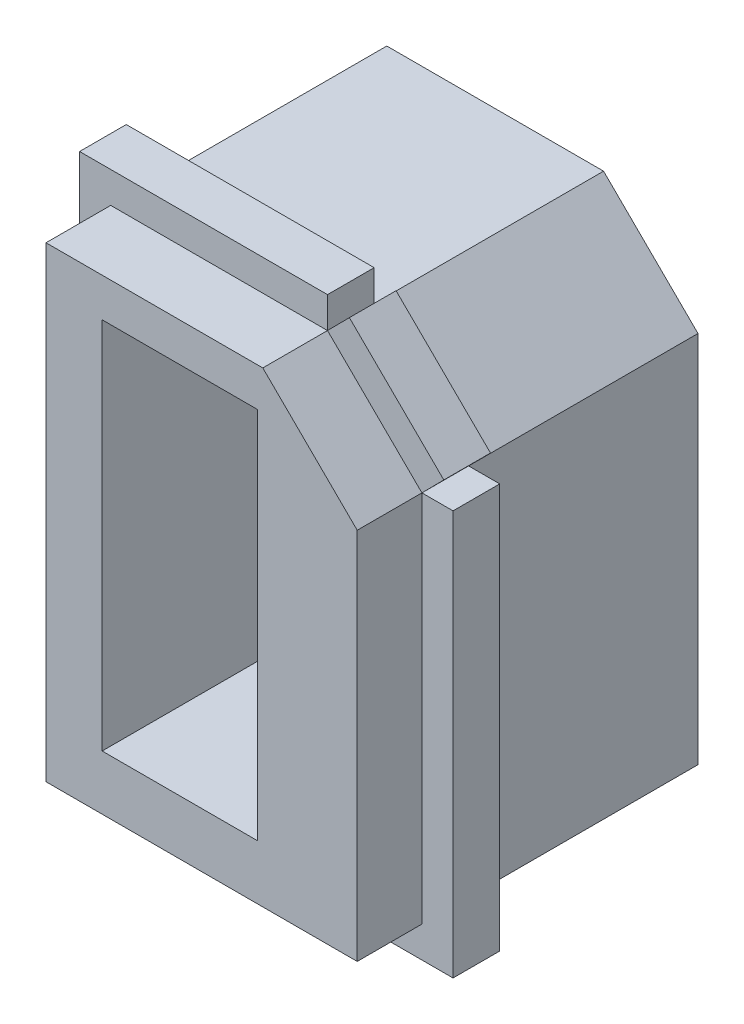
SolidWorks part; units mm, degrees
ref_plane "Front Plane" through (0, 0, 0) normal (0, 0, 1) x (1, 0, 0)
ref_plane "Top Plane" through (0, 0, 0) normal (0, 1, 0) x (1, 0, 0)
ref_plane "Right Plane" through (0, 0, 0) normal (1, 0, 0) x (0, 0, -1)
sketch "Sketch1" plane through (0, 0, 0) normal (0, 0, 1) x (1, 0, 0)
  line L0 (0, 0) -> (-10, 0)
  line L1 (-10, 0) -> (-10, 15)
  line L2 (0, 0) -> (0, 12)
  line L3 (-10, 15) -> (-3.034, 15)
  line L4 (-3.034, 15) -> (0, 12)
  line L5 (-8.1964, 1.7581) -> (-8.1964, 13.7581)
  line L13 (-3.1964, 1.7581) -> (-8.1964, 1.7581)
  line L15 (-8.1964, 13.7581) -> (-3.1964, 13.7581)
  line L16 (-3.1964, 13.7581) -> (-3.1964, 1.7581)
  dimension "D1" = 12
  dimension "D2" = 5
  dimension "D3" = 5
  dimension "D4" = 10
  dimension "D5" = 15
  dimension "D6" = 12
extrude "Boss-Extrude1" add sketch "Sketch1" along normal blind 10.95
sketch "Sketch2" plane through (0, 0, 0) normal (1, 0, 0) x (0, 0, -1)
sketch "Sketch3" plane through (-10, 0, 0) normal (-1, 0, 0) x (0, 0, 1)
  line L0 (10.95, 15) -> (8.8709, 15)
  line L1 (10.95, 15) -> (0, 15) construction
  line L2 (8.8709, 15) -> (8.8709, 0)
  line L3 (10.95, 0) -> (0, 0) construction
  line L4 (8.8709, 15) -> (7.3709, 15)
  line L5 (7.3709, 15) -> (7.3709, 0)
  line L6 (7.3709, 0) -> (8.8709, 0)
sketch "Sketch4" plane through (0, 0, 0) normal (0, -1, 0) x (1, 0, 0)
  line L0 (-10, 8.8709) -> (0, 8.8709)
  line L1 (-10, 7.3709) -> (-10, 8.8709)
  line L2 (-10, 7.3709) -> (-10, 8.8709) construction
  line L3 (-10, 10.95) -> (-10, 0) construction
  line L4 (0, 10.95) -> (0, 0) construction
  line L5 (-10, 7.3709) -> (0, 7.3709)
  line L6 (0, 7.3709) -> (0, 8.8709)
sketch "Sketch5" plane through (0, 0, 0) normal (1, 0, 0) x (0, 0, -1)
  line L0 (-8.8709, 0) -> (-8.8709, 12)
  line L1 (-10.95, 12) -> (0, 12) construction
  line L2 (-7.3709, 0) -> (-7.3709, 12)
sketch "Sketch6" plane through (0, 15, 0) normal (0, 1, 0) x (1, 0, 0)
  line L0 (-10, -8.8709) -> (-3.034, -8.8709)
  line L1 (-10, -10.95) -> (-10, -8.8709) construction
  line L2 (-10, -8.8709) -> (-10, -7.3709) construction
  line L3 (-3.034, -10.95) -> (-3.034, 0) construction
  line L4 (-10, -7.3709) -> (-3.034, -7.3709)
  line L5 (-3.034, -7.3709) -> (-3.034, -8.8709)
  line L6 (-10, -8.8709) -> (-10, -7.3709)
extrude "Boss-Extrude2" add sketch "Sketch6" along normal blind 1
extrude "Boss-Extrude4" add sketch "Sketch4" along normal blind 1 contours L5 L6 L0 L1
sketch "Sketch9" plane through (-10, 0, 0) normal (-1, 0, 0) x (0, 0, 1)
  line L0 (8.8709, -1) -> (8.8709, 16)
  line L1 (8.8709, 16) -> (7.3709, 16)
  line L2 (7.3709, 16) -> (7.3709, -1)
  line L3 (7.3709, -1) -> (8.8709, -1)
extrude "Boss-Extrude5" add sketch "Sketch9" along normal blind 1
sketch "Sketch10" plane through (0, 0, 0) normal (1, 0, 0) x (0, 0, -1)
  line L0 (-8.8709, 12) -> (-8.8709, -1)
  line L1 (-8.8709, -1) -> (-7.3709, -1)
  line L2 (-7.3709, -1) -> (-8.8709, -1) construction
  line L3 (-7.3709, -1) -> (-7.3709, 12)
  line L4 (-7.3709, 12) -> (-8.8709, 12)
extrude "Boss-Extrude6" add sketch "Sketch10" along normal blind 1
sketch "Sketch11" plane through (5.9996, 6.0676, 0) normal (0.7031, 0.7111, 0) x (0.7111, -0.7031, 0)
  line L0 (-12.7041, -7.3709) -> (-8.4374, -7.3709)
  line L1 (-12.7041, -8.8709) -> (-8.4374, -8.8709)
  line L2 (-12.7041, -8.8709) -> (-12.7041, -7.3709)
  line L3 (-8.4374, -8.8709) -> (-8.4374, -7.3709)
extrude "Boss-Extrude7" add sketch "Sketch11" along normal blind 1
